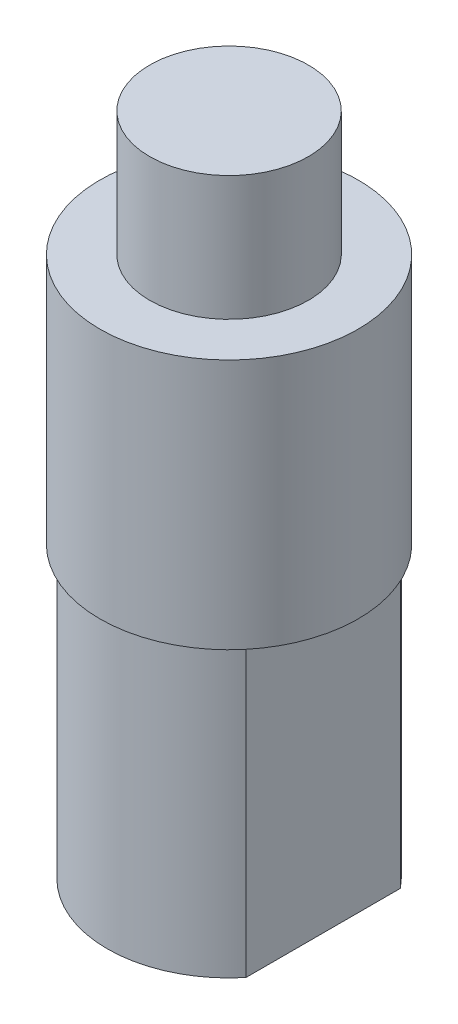
SolidWorks part; units mm, degrees
ref_plane "Front Plane" through (0, 0, 0) normal (0, 0, 1) x (1, 0, 0)
ref_plane "Top Plane" through (0, 0, 0) normal (0, 1, 0) x (1, 0, 0)
ref_plane "Right Plane" through (0, 0, 0) normal (1, 0, 0) x (0, 0, -1)
other "Bounding Box"
ref_plane "Default Plane" through (-8.9266, -12.7485, 0) normal (-0.1736, 0.9848, 0) x (0.9848, 0.1736, 0)
sketch "Sketch1" plane through (0, 0, 0) normal (0, 1, 0) x (1, 0, 0)
  circle A0 centre (0, 0) radius 8.3
  dimension "D1" = 16.6
extrude "Boss-Extrude1" add sketch "Sketch1" against normal blind 16.125
sketch "Sketch2" plane through (0, 0, 0) normal (0, 1, 0) x (1, 0, 0)
  circle A0 centre (0, 0) radius 5.1
  dimension "D1" = 10.2
extrude "Boss-Extrude2" add sketch "Sketch2" along normal blind 8
sketch "Sketch3" plane through (0, -16.125, 0) normal (0, -1, 0) x (1, 0, 0)
  line L0 (-6.05, -4.9627) -> (-6.05, 4.9627)
  line L1 (6.05, -4.9627) -> (6.05, 4.9627)
  arc A0 (-6.05, -4.9627) -> (6.05, -4.9627) centre (0, 0) ccw
  arc A1 (6.05, 4.9627) -> (-6.05, 4.9627) centre (0, 0) ccw
  dimension "D1" = 7.825
  dimension "D2" = 12.1
extrude "Boss-Extrude3" add sketch "Sketch3" along normal blind 18.6
